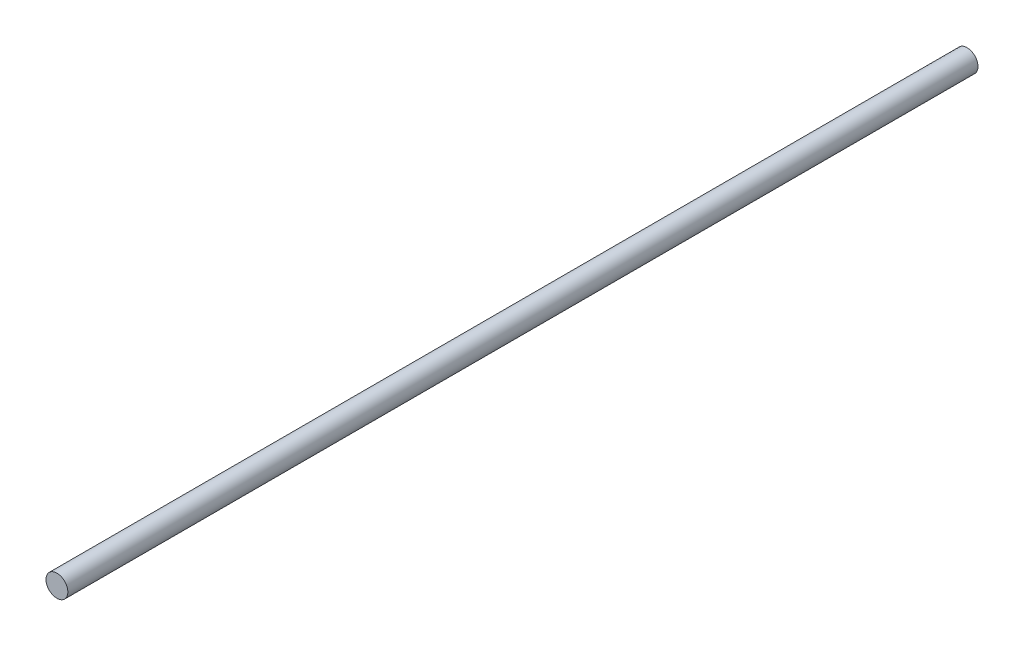
SolidWorks part; units mm, degrees
ref_plane "Plano frontal" through (0, 0, 0) normal (0, 0, 1) x (1, 0, 0)
ref_plane "Plano superior" through (0, 0, 0) normal (0, 1, 0) x (1, 0, 0)
ref_plane "Plano direito" through (0, 0, 0) normal (1, 0, 0) x (0, 0, -1)
sketch "Esboço1" plane through (0, 0, 0) normal (0, 0, 1) x (1, 0, 0)
  circle A0 centre (0, 0) radius 6
  dimension "D1" = 12
extrude "Ressalto-extrusão1" add sketch "Esboço1" along normal blind 500
